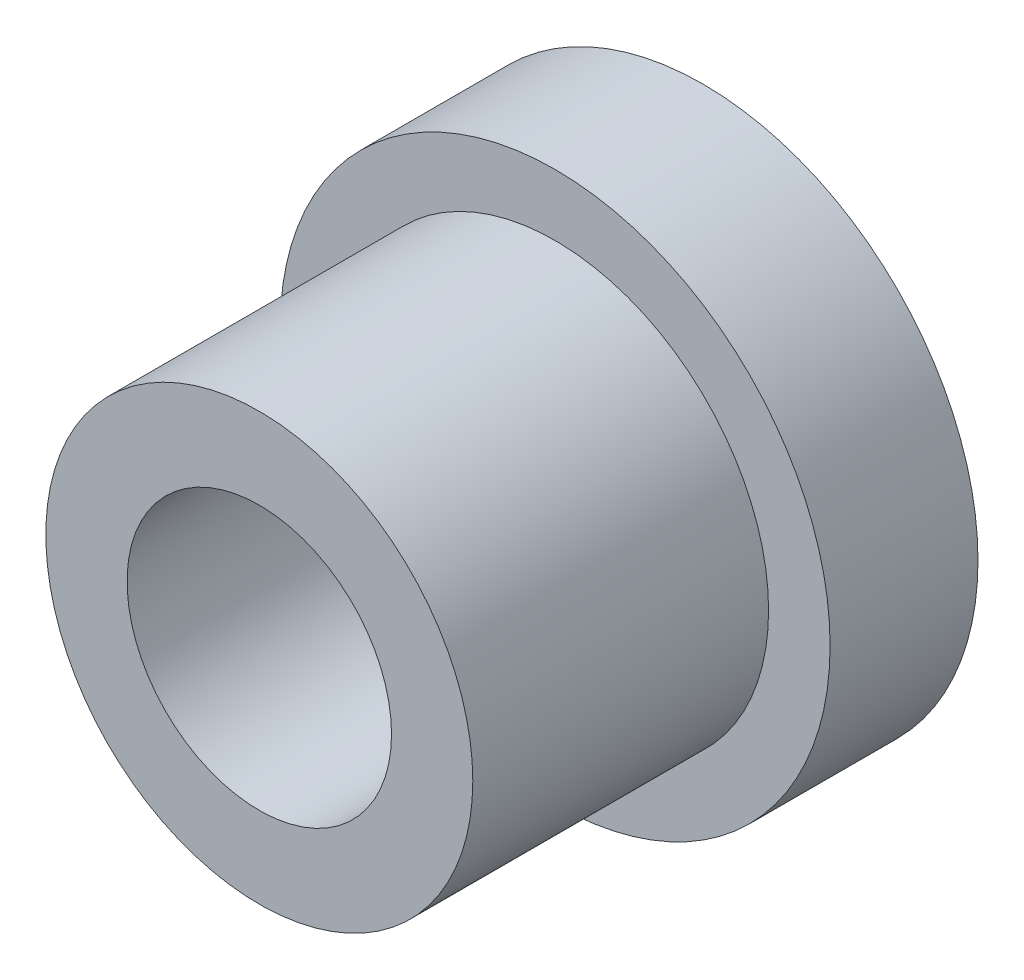
SolidWorks part; units mm, degrees
ref_plane "Front Plane" through (0, 0, 0) normal (0, 0, 1) x (1, 0, 0)
ref_plane "Top Plane" through (0, 0, 0) normal (0, 1, 0) x (1, 0, 0)
ref_plane "Right Plane" through (0, 0, 0) normal (1, 0, 0) x (0, 0, -1)
sketch "Sketch1" plane through (0, 0, 0) normal (0, 0, 1) x (1, 0, 0)
  circle A0 centre (0, 0) radius 7.2175
  circle A1 centre (0, 0) radius 4.47
  dimension "D1" = 8.94
extrude "Boss-Extrude1" add sketch "Sketch1" along normal blind 10
sketch "Sketch2" plane through (0, 0, 0) normal (0, 0, -1) x (-1, 0, 0)
  circle A0 centre (0, 0) radius 9.297
extrude "Boss-Extrude2" add sketch "Sketch2" along normal blind 5
